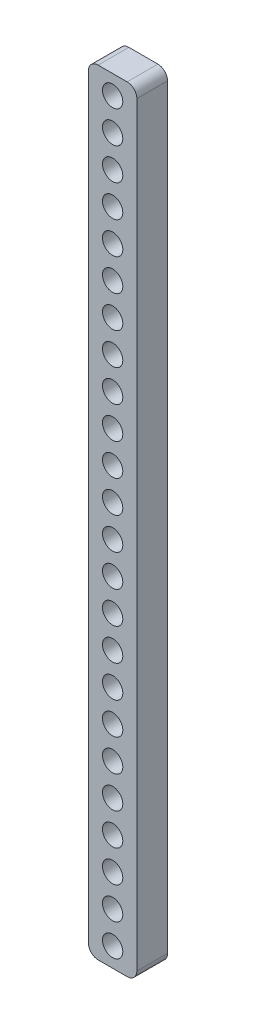
SolidWorks part; units mm, degrees
ref_plane "Front Plane" through (0, 0, 0) normal (0, 0, 1) x (1, 0, 0)
ref_plane "Top Plane" through (0, 0, 0) normal (0, 1, 0) x (1, 0, 0)
ref_plane "Right Plane" through (0, 0, 0) normal (1, 0, 0) x (0, 0, -1)
sketch "Sketch1" plane through (0, 0, 0) normal (0, 0, 1) x (1, 0, 0)
  line L0 (0, -80) -> (0, 80) construction
  line L1 (3, -80) -> (-3, -80)
  line L2 (5, -78) -> (5, 78)
  line L3 (3, 80) -> (-3, 80)
  line L4 (-5, -78) -> (-5, 78)
  line L5 (5, -80) -> (-5, 80) construction
  line L6 (5, 80) -> (-5, -80) construction
  circle A1 centre (0, 76) radius 2.1
  circle A2 centre (0, 69.3913) radius 2.1
  circle A3 centre (0, 62.7826) radius 2.1
  circle A4 centre (0, 56.1739) radius 2.1
  circle A5 centre (0, 49.5652) radius 2.1
  circle A6 centre (0, 42.9565) radius 2.1
  circle A7 centre (0, 36.3478) radius 2.1
  circle A8 centre (0, 29.7391) radius 2.1
  circle A9 centre (0, 23.1304) radius 2.1
  circle A10 centre (0, 16.5217) radius 2.1
  circle A11 centre (0, 9.913) radius 2.1
  circle A12 centre (0, 3.3043) radius 2.1
  circle A13 centre (0, -3.3043) radius 2.1
  circle A14 centre (0, -9.913) radius 2.1
  circle A15 centre (0, -16.5217) radius 2.1
  circle A16 centre (0, -23.1304) radius 2.1
  circle A17 centre (0, -29.7391) radius 2.1
  circle A18 centre (0, -36.3478) radius 2.1
  circle A19 centre (0, -42.9565) radius 2.1
  circle A20 centre (0, -49.5652) radius 2.1
  circle A21 centre (0, -56.1739) radius 2.1
  circle A22 centre (0, -62.7826) radius 2.1
  circle A23 centre (0, -69.3913) radius 2.1
  circle A24 centre (0, -76) radius 2.1
  arc A25 (-3, -80) -> (-5, -78) centre (-3, -78) cw
  arc A26 (3, -80) -> (5, -78) centre (3, -78) ccw
  arc A27 (5, 78) -> (3, 80) centre (3, 78) ccw
  arc A28 (-3, 80) -> (-5, 78) centre (-3, 78) ccw
  point P0 (0, 0)
  point P10 (0, 69.5286)
  dimension "D3" = 4.2
  dimension "D7" = 2
  dimension "D1" = 160
  dimension "D2" = 10
  dimension "D4" = 4
  dimension "D6" = 4
  dimension "D5" = 24
extrude "Boss-Extrude1" add sketch "Sketch1" along normal blind 6.35
